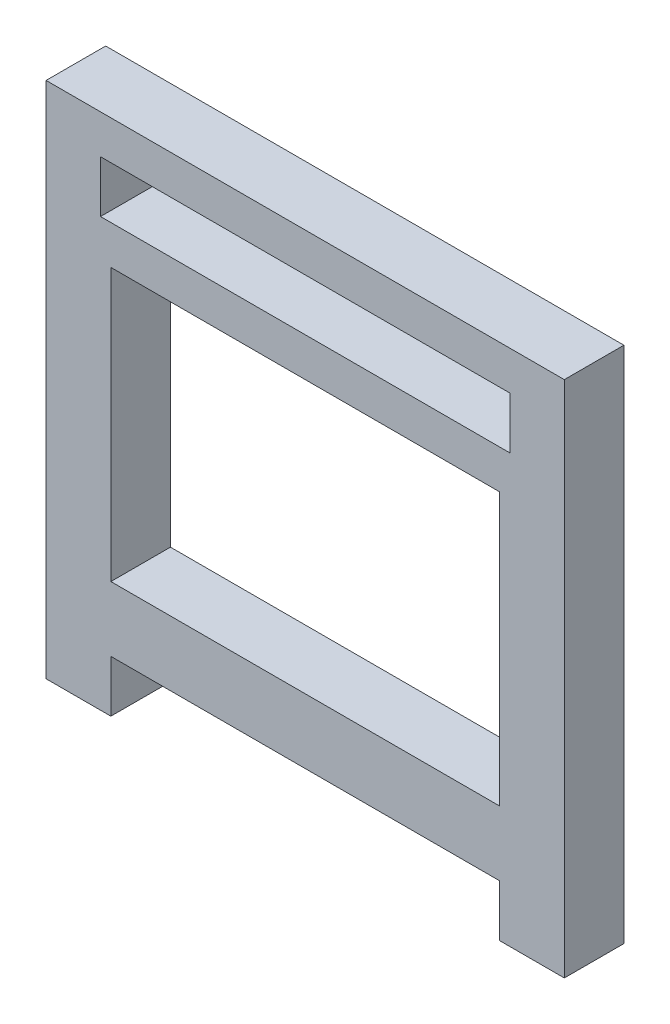
SolidWorks part; units mm, degrees
ref_plane "Front Plane" through (0, 0, 0) normal (0, 0, 1) x (1, 0, 0)
ref_plane "Top Plane" through (0, 0, 0) normal (0, 1, 0) x (1, 0, 0)
ref_plane "Right Plane" through (0, 0, 0) normal (1, 0, 0) x (0, 0, -1)
sketch "Sketch1" plane through (0, 0, 0) normal (0, 0, 1) x (1, 0, 0)
  line L0 (0, 0) -> (0, -2)
  line L1 (2.5, 0) -> (17.5, 0)
  line L2 (0, 0) -> (0, 18)
  line L3 (0, 18) -> (20, 18)
  line L4 (20, 0) -> (20, 18)
  line L5 (0, -2) -> (2.5, -2)
  line L6 (2.5, -2) -> (2.5, 0)
  line L7 (20, 0) -> (20, -2)
  line L8 (20, -2) -> (17.5, -2)
  line L9 (17.5, -2) -> (17.5, 0)
  line L12 (2.5, 2.5) -> (17.5, 2.5)
  line L13 (2.5, 2.5) -> (2.5, 13)
  line L14 (2.5, 13) -> (17.5, 13)
  line L15 (17.5, 2.5) -> (17.5, 13)
  line L16 (2.1, 14.5) -> (17.9, 14.5)
  line L17 (2.1, 14.5) -> (2.1, 16.5)
  line L18 (2.1, 16.5) -> (17.9, 16.5)
  line L19 (17.9, 14.5) -> (17.9, 16.5)
  dimension "D1" = 18
  dimension "D2" = 20
  dimension "D3" = 15
  dimension "D4" = 2
  dimension "D5" = 2
  dimension "D7" = 2.5
  dimension "D8" = 10.5
  dimension "D9" = 2
  dimension "D10" = 1.5
  dimension "D11" = 15.8
extrude "Boss-Extrude1" add sketch "Sketch1" along normal blind 2.3
